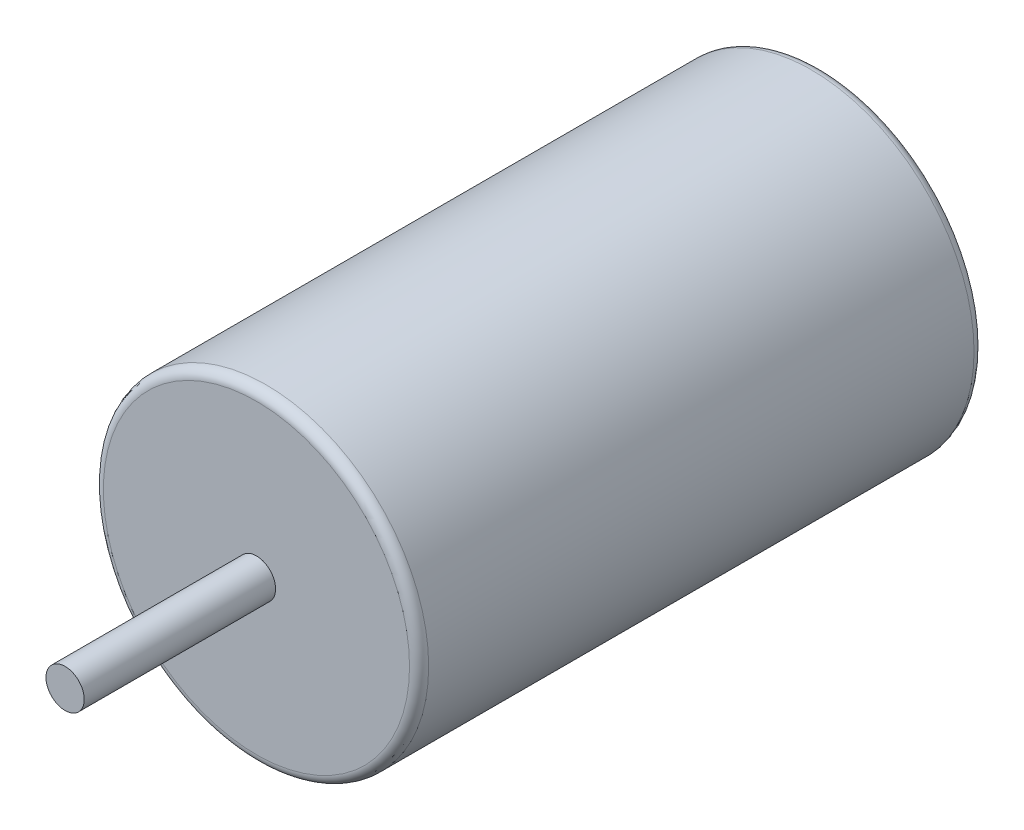
SolidWorks part; units mm, degrees
ref_plane "Front Plane" through (0, 0, 0) normal (0, 0, 1) x (1, 0, 0)
ref_plane "Top Plane" through (0, 0, 0) normal (0, 1, 0) x (1, 0, 0)
ref_plane "Right Plane" through (0, 0, 0) normal (1, 0, 0) x (0, 0, -1)
sketch "Sketch1" plane through (0, 0, 0) normal (0, 0, 1) x (1, 0, 0)
  circle A0 centre (0, 0) radius 34
  dimension "D1" = 68
extrude "Boss-Extrude1" add sketch "Sketch1" along normal blind 118
sketch "Sketch2" plane through (0, 0, 118) normal (0, 0, 1) x (1, 0, 0)
  circle A0 centre (0, 0) radius 4
  dimension "D1" = 8
extrude "Boss-Extrude2" add sketch "Sketch2" along normal blind 40
fillet "Fillet1" radius 2 2 edges at (34, 0, 118) (34, 0, 0)
